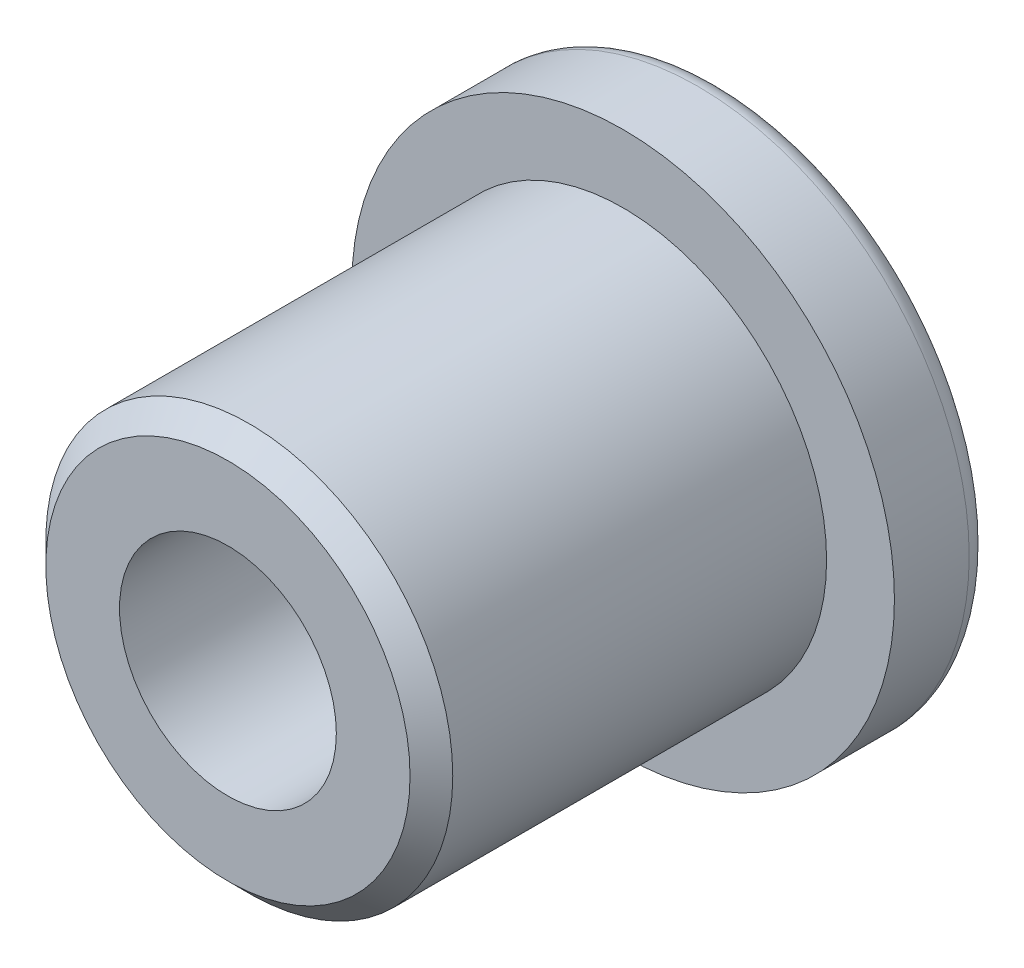
SolidWorks part; units mm, degrees
ref_plane "정면" through (0, 0, 0) normal (0, 0, 1) x (1, 0, 0)
ref_plane "윗면" through (0, 0, 0) normal (0, 1, 0) x (1, 0, 0)
ref_plane "우측면" through (0, 0, 0) normal (1, 0, 0) x (0, 0, -1)
sketch "스케치1" plane through (0, 0, 0) normal (0, 0, 1) x (1, 0, 0)
  circle A0 centre (0, 0) radius 12.7
  circle A1 centre (0, 0) radius 3.75
  dimension "D1" = 7.5
  dimension "D2" = 25.4
extrude "보스-돌출1" add sketch "스케치1" along normal blind 3
sketch "스케치2" plane through (0, 0, 3) normal (0, 0, 1) x (1, 0, 0)
  circle A0 centre (0, 0) radius 9.525
  circle A1 centre (0, 0) radius 5.075
  dimension "D1" = 19.05
  dimension "D2" = 10.15
extrude "보스-돌출2" add sketch "스케치2" along normal blind 20
chamfer "모따기1" distance 1 angle 45 1 edges at (9.525, 0, 23)
fillet "필렛1" radius 1 1 edges at (12.7, 0, 0)
sketch "스케치3" plane through (0, 0, 3) normal (0, 0, 1) x (1, 0, 0)
  circle A0 centre (0, 0) radius 9.525
  circle A1 centre (0, 0) radius 12.7
  circle A2 centre (0, 0) radius 9.525 construction
  circle A3 centre (0, 0) radius 12.7 construction
extrude "보스-돌출3" add sketch "스케치3" along normal blind 1.5
sketch "스케치4" plane through (0, 0, 3) normal (0, 0, 1) x (1, 0, 0)
  circle A0 centre (0, 0) radius 5.075
  circle A1 centre (0, 0) radius 3.75
  circle A2 centre (0, 0) radius 3.75 construction
  circle A3 centre (0, 0) radius 5.075 construction
extrude "보스-돌출4" add sketch "스케치4" along normal blind 7.8
sketch "스케치5" plane through (0, 0, 0) normal (0, 0, -1) x (-1, 0, 0)
  circle A0 centre (0, 0) radius 5.5
  dimension "D1" = 11
extrude "컷-돌출1" cut sketch "스케치5" against normal blind 7.5
chamfer "모따기2" distance 1 angle 45 2 edges at (-5.5, 0, 0) (-5.5, 0, 7.5)
